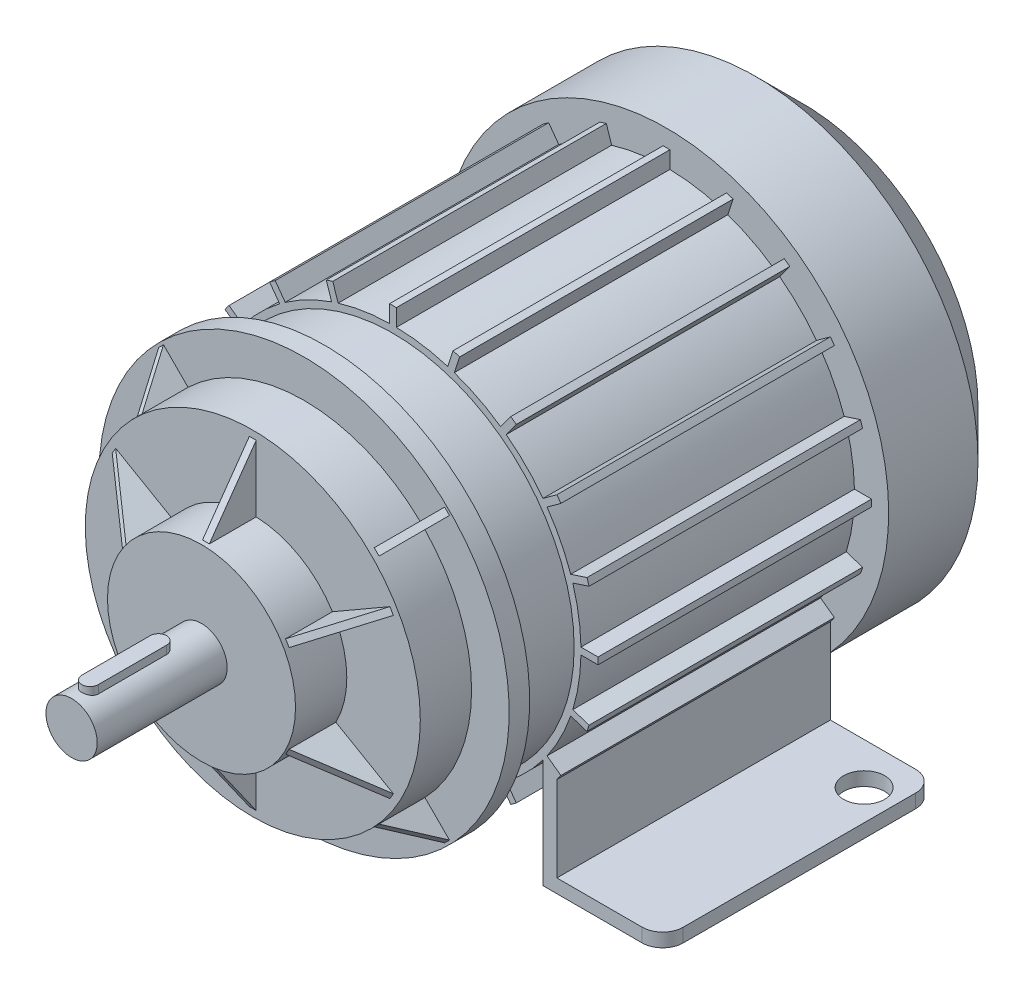
SolidWorks part; units mm, degrees
ref_plane "Front Plane" through (0, 0, 0) normal (0, 0, 1) x (1, 0, 0)
ref_plane "Top Plane" through (0, 0, 0) normal (0, 1, 0) x (1, 0, 0)
ref_plane "Right Plane" through (0, 0, 0) normal (1, 0, 0) x (0, 0, -1)
sketch "Sketch1" plane through (0, 0, 0) normal (0, 0, 1) x (1, 0, 0)
  circle A0 centre (0, 0) radius 82.55
  dimension "D1" = 165.1
extrude "Boss-Extrude1" add sketch "Sketch1" along normal blind 50.8 contours A0
chamfer "Chamfer1" distance 17.62 angle 45 1 edges at (82.55, 0, 0)
sketch "Sketch2" plane through (0, 0, 50.8) normal (0, 0, 1) x (1, 0, 0)
  line L0 (0, 69.85) -> (0, 76.2) construction
  line L1 (1.27, 76.1894) -> (1.27, 69.8385)
  line L2 (-1.27, 76.1894) -> (-1.27, 69.8385)
  line L3 (76.1894, 1.27) -> (69.8385, 1.27)
  line L4 (76.1894, -1.27) -> (69.8385, -1.27)
  line L5 (1.27, -76.1894) -> (1.27, -69.8385)
  line L6 (-1.27, -76.1894) -> (-1.27, -69.8385)
  line L7 (-76.1894, -1.27) -> (-69.8385, -1.27)
  line L8 (-76.1894, 1.27) -> (-69.8385, 1.27)
  line L9 (22.336, 72.8529) -> (20.3734, 66.8128)
  line L10 (24.7517, 72.068) -> (22.7891, 66.0279)
  line L11 (43.7556, 62.385) -> (40.0226, 57.247)
  line L12 (45.8105, 60.892) -> (42.0775, 55.754)
  line L13 (60.892, 45.8105) -> (55.754, 42.0775)
  line L14 (62.385, 43.7556) -> (57.247, 40.0226)
  line L15 (72.068, 24.7517) -> (66.0279, 22.7891)
  line L16 (72.8529, 22.336) -> (66.8128, 20.3734)
  line L17 (76.1894, 1.27) -> (69.8385, 1.27)
  line L18 (76.1894, -1.27) -> (69.8385, -1.27)
  line L19 (72.8529, -22.336) -> (66.8128, -20.3734)
  line L20 (72.068, -24.7517) -> (66.0279, -22.7891)
  line L21 (62.385, -43.7556) -> (57.247, -40.0226)
  line L22 (60.892, -45.8105) -> (55.754, -42.0775)
  line L23 (45.8105, -60.892) -> (42.0775, -55.754)
  line L24 (43.7556, -62.385) -> (40.0226, -57.247)
  line L25 (24.7517, -72.068) -> (22.7891, -66.0279)
  line L26 (22.336, -72.8529) -> (20.3734, -66.8128)
  line L27 (1.27, -76.1894) -> (1.27, -69.8385)
  line L28 (-1.27, -76.1894) -> (-1.27, -69.8385)
  line L29 (-22.336, -72.8529) -> (-20.3734, -66.8128)
  line L30 (-24.7517, -72.068) -> (-22.7891, -66.0279)
  line L31 (-43.7556, -62.385) -> (-40.0226, -57.247)
  line L32 (-45.8105, -60.892) -> (-42.0775, -55.754)
  line L33 (-60.892, -45.8105) -> (-55.754, -42.0775)
  line L34 (-62.385, -43.7556) -> (-57.247, -40.0226)
  line L35 (-72.068, -24.7517) -> (-66.0279, -22.7891)
  line L36 (-72.8529, -22.336) -> (-66.8128, -20.3734)
  line L37 (-76.1894, -1.27) -> (-69.8385, -1.27)
  line L38 (-76.1894, 1.27) -> (-69.8385, 1.27)
  line L39 (-72.8529, 22.336) -> (-66.8128, 20.3734)
  line L40 (-72.068, 24.7517) -> (-66.0279, 22.7891)
  line L41 (-62.385, 43.7556) -> (-57.247, 40.0226)
  line L42 (-60.892, 45.8105) -> (-55.754, 42.0775)
  line L43 (-45.8105, 60.892) -> (-42.0775, 55.754)
  line L44 (-43.7556, 62.385) -> (-40.0226, 57.247)
  line L45 (-24.7517, 72.068) -> (-22.7891, 66.0279)
  line L46 (-22.336, 72.8529) -> (-20.3734, 66.8128)
  arc A0 (-60.892, 45.8105) -> (-62.385, 43.7556) centre (0, 0) ccw
  arc A1 (-42.0775, 55.754) -> (-55.754, 42.0775) centre (0, 0) ccw
  arc A2 (-43.7556, 62.385) -> (-45.8105, 60.892) centre (0, 0) ccw
  arc A3 (-57.247, 40.0226) -> (-66.0279, 22.7891) centre (0, 0) ccw
  arc A4 (-22.336, 72.8529) -> (-24.7517, 72.068) centre (0, 0) ccw
  arc A5 (-22.7891, 66.0279) -> (-40.0226, 57.247) centre (0, 0) ccw
  arc A6 (-1.27, 69.8385) -> (-20.3734, 66.8128) centre (0, 0) ccw
  arc A7 (1.27, 76.1894) -> (-1.27, 76.1894) centre (0, 0) ccw
  arc A8 (24.7517, 72.068) -> (22.336, 72.8529) centre (0, 0) ccw
  arc A9 (45.8105, 60.892) -> (43.7556, 62.385) centre (0, 0) ccw
  arc A10 (20.3734, 66.8128) -> (1.27, 69.8385) centre (0, 0) ccw
  arc A11 (62.385, 43.7556) -> (60.892, 45.8105) centre (0, 0) ccw
  arc A12 (72.8529, 22.336) -> (72.068, 24.7517) centre (0, 0) ccw
  arc A13 (40.0226, 57.247) -> (22.7891, 66.0279) centre (0, 0) ccw
  arc A14 (55.754, 42.0775) -> (42.0775, 55.754) centre (0, 0) ccw
  arc A15 (66.0279, 22.7891) -> (57.247, 40.0226) centre (0, 0) ccw
  arc A16 (60.892, -45.8105) -> (62.385, -43.7556) centre (0, 0) ccw
  arc A17 (72.068, -24.7517) -> (72.8529, -22.336) centre (0, 0) ccw
  arc A18 (76.1894, -1.27) -> (76.1894, 1.27) centre (0, 0) ccw
  arc A19 (66.8128, -20.3734) -> (69.8385, -1.27) centre (0, 0) ccw
  arc A20 (69.8385, 1.27) -> (66.8128, 20.3734) centre (0, 0) ccw
  arc A21 (57.247, -40.0226) -> (66.0279, -22.7891) centre (0, 0) ccw
  arc A22 (42.0775, -55.754) -> (55.754, -42.0775) centre (0, 0) ccw
  arc A23 (22.7891, -66.0279) -> (40.0226, -57.247) centre (0, 0) ccw
  arc A24 (-66.8128, 20.3734) -> (-69.8385, 1.27) centre (0, 0) ccw
  arc A25 (-72.068, 24.7517) -> (-72.8529, 22.336) centre (0, 0) ccw
  arc A26 (-72.8529, -22.336) -> (-72.068, -24.7517) centre (0, 0) ccw
  arc A27 (-66.0279, -22.7891) -> (-57.247, -40.0226) centre (0, 0) ccw
  arc A28 (-62.385, -43.7556) -> (-60.892, -45.8105) centre (0, 0) ccw
  arc A29 (-45.8105, -60.892) -> (-43.7556, -62.385) centre (0, 0) ccw
  arc A30 (-55.754, -42.0775) -> (-42.0775, -55.754) centre (0, 0) ccw
  arc A31 (-40.0226, -57.247) -> (-22.7891, -66.0279) centre (0, 0) ccw
  arc A32 (-24.7517, -72.068) -> (-22.336, -72.8529) centre (0, 0) ccw
  arc A33 (-1.27, -76.1894) -> (1.27, -76.1894) centre (0, 0) ccw
  arc A34 (22.336, -72.8529) -> (24.7517, -72.068) centre (0, 0) ccw
  arc A35 (1.27, -69.8385) -> (20.3734, -66.8128) centre (0, 0) ccw
  arc A36 (-20.3734, -66.8128) -> (-1.27, -69.8385) centre (0, 0) ccw
  arc A37 (43.7556, -62.385) -> (45.8105, -60.892) centre (0, 0) ccw
  arc A38 (-69.8385, -1.27) -> (-66.8128, -20.3734) centre (0, 0) ccw
  arc A39 (-76.1894, 1.27) -> (-76.1894, -1.27) centre (0, 0) ccw
  point P25 (0, 0)
  point P102 (0, 0)
  dimension "D1" = 152.4
  dimension "D2" = 139.7
  dimension "D3" = 1.27
  dimension "D4" = 4
  dimension "D5" = 20
extrude "Boss-Extrude2" add sketch "Sketch2" along normal blind 101.6 contours L8 A39 L7 A38 L36 A26 L35 A27 L34 A28 L33 A30 L32 A29 L31 A31 L30 A32 L29 A36 L6 A33 L5 A35 L26 A34 L25 A23 L24 A37 L23 A22 L22 A16 L21 A21 L20 A17 L19 A19 L4 A18 L3 A20 L16 A12 L15 A15 L14 A11 L13
sketch "Sketch19" plane through (0, 0, 50.8) normal (0, 0, 1) x (1, 0, 0)
  line L0 (60.892, -45.8105) -> (55.754, -42.0775) construction
  line L1 (60.892, -45.8105) -> (55.754, -42.0775)
  line L2 (0, -82.55) -> (100.204, -82.55) construction
  line L3 (55.754, -42.0775) -> (55.754, -82.55)
  line L4 (55.754, -82.55) -> (100.204, -82.55)
  line L5 (100.204, -82.55) -> (100.204, -77.47)
  line L6 (100.204, -77.47) -> (60.892, -77.47)
  line L7 (60.892, -77.47) -> (60.892, -45.8105)
  line L8 (0, 0) -> (0, -82.55) construction
  line L9 (-100.204, -82.55) -> (-100.204, -77.47)
  line L10 (-55.754, -82.55) -> (-100.204, -82.55)
  line L11 (-100.204, -77.47) -> (-60.892, -77.47)
  line L12 (-60.892, -77.47) -> (-60.892, -45.8105)
  line L13 (-60.892, -45.8105) -> (-55.754, -42.0775)
  line L14 (-55.754, -42.0775) -> (-55.754, -82.55)
  circle A0 centre (0, 0) radius 82.55 construction
  dimension "D1" = 5.08
  dimension "D2" = 44.45
  dimension "D3" = 40.4725
extrude "Boss-Extrude8" add sketch "Sketch19" along normal up to surface (101.6 mm away) up to face at (0, 0, 152.4)
fillet "Fillet1" radius 7.62 4 edges at (-100.204, -80.01, 50.8) (-100.204, -80.01, 152.4) (100.204, -80.01, 50.8) (100.204, -80.01, 152.4)
sketch "Sketch4" plane through (0, 0, 152.4) normal (0, 0, 1) x (1, 0, 0)
  circle A0 centre (0, 0) radius 67.31
  dimension "D1" = 134.62
extrude "Boss-Extrude3" add sketch "Sketch4" along normal blind 25.4
sketch "Sketch5" plane through (0, 0, 177.8) normal (0, 0, 1) x (1, 0, 0)
  circle A0 centre (0, 0) radius 76.2
extrude "Boss-Extrude4" add sketch "Sketch5" along normal blind 7.62
sketch "Sketch6" plane through (0, 0, 185.42) normal (0, 0, 1) x (1, 0, 0)
  circle A0 centre (0, 0) radius 62.23
  dimension "D1" = 124.46
extrude "Boss-Extrude5" add sketch "Sketch6" along normal blind 19.05
sketch "Sketch8" plane through (0, 0, 204.47) normal (0, 0, 1) x (1, 0, 0)
  circle A0 centre (0, 0) radius 34.925
  dimension "D1" = 69.85
extrude "Boss-Extrude6" add sketch "Sketch8" along normal blind 19.05
ref_plane "Plane1" through (0, 0, 0) normal (1, 0, 0) x (0, 0, -1)
sketch "Sketch15" plane through (0, 0, 0) normal (1, 0, 0) x (0, 0, -1)
  line L0 (-223.52, 32.5953) -> (-204.47, 32.5953) construction
  line L1 (-223.52, 34.925) -> (-223.52, -34.925) construction
  line L2 (-204.47, 34.925) -> (-204.47, -34.925) construction
  line L3 (-204.47, 32.5953) -> (-202.6512, 32.5953) construction
  line L4 (-202.6512, 32.5953) -> (-202.6512, 62.1305) construction
  line L5 (-204.47, 62.23) -> (-204.47, -62.23) construction
  line L6 (-204.47, 34.925) -> (-223.52, 34.925) construction
  line L7 (-223.52, 32.5953) -> (-202.6512, 62.1305)
  dimension "D1" = 1.8188
  dimension "D2" = 2.3297
  dimension "D3" = 29.5352
rib "Rib9" sketch "Sketch15" sketch "Sketch15" thickness 2.54 extrusion direction parallel to sketch draft on no parameters "D1"=2.54
pattern_circular "CirPattern1" count 6 over 360 about axis through (0, 0, 0) along (0, 0, 1) of "Rib9"
sketch "Sketch16" plane through (0, 0, 0) normal (1, 0, 0) x (0, 0, -1)
  line L0 (-262.2923, 0) -> (62.6805, 0) construction
ref_plane "Plane2" through (0, 0, 0) normal (0.7071, -0.7071, 0) x (0, 0, -1)
sketch "Sketch17" plane through (0, 0, 0) normal (0.7071, -0.7071, 0) x (0, 0, -1)
  line L0 (-204.47, 60.7051) -> (-183.9829, 60.7051) construction
  line L1 (-204.47, 62.23) -> (-204.47, -62.23) construction
  line L2 (-183.9829, 60.7051) -> (-183.9829, 76.2) construction
  line L4 (-262.2923, 0) -> (62.6805, 0) construction
  line L5 (-204.47, 60.7051) -> (-183.9829, 76.2)
  dimension "D1" = 20.4871
  dimension "D2" = 60.7051
  dimension "D3" = 15.4949
rib "Rib10" sketch "Sketch17" sketch "Sketch17" thickness 2.54 extrusion direction parallel to sketch draft on no parameters "D1"=2.54
pattern_circular "CirPattern2" count 4 over 360 about axis through (0, 0, 0) along (0, 0, 1) of "Rib10"
sketch "Sketch18" plane through (0, 0, 223.52) normal (0, 0, 1) x (1, 0, 0)
  circle A0 centre (0, 0) radius 9.525
  dimension "D1" = 19.05
extrude "Boss-Extrude7" add sketch "Sketch18" along normal blind 48.26
sketch "Sketch20" plane through (0, -77.47, 0) normal (0, 1, 0) x (1, 0, 0)
  line L0 (88.8598, -50.8) -> (88.8598, -66.2277) construction
  line L1 (92.584, -50.8) -> (60.892, -50.8) construction
  line L2 (88.8598, -66.2277) -> (100.204, -66.2277) construction
  line L3 (100.204, -144.78) -> (100.204, -58.42) construction
  circle A0 centre (88.8598, -66.2277) radius 7.6228
  dimension "D3" = 15.2456
  dimension "D1" = 11.3442
  dimension "D2" = 15.4277
extrude "Cut-Extrude1" cut sketch "Sketch20" against normal through all
mirror "Mirror1" about plane through (0, 0, 0) normal (1, 0, 0) of "Cut-Extrude1"
sketch "Sketch21" plane through (0, 0, 0) normal (0, 1, 0) x (1, 0, 0)
  line L0 (0, -286.2576) -> (0, -223.52) construction
  line L1 (-9.525, -223.52) -> (9.525, -223.52) construction
  line L2 (0, -264.922) -> (0, -239.522) construction
  line L3 (-3.048, -264.922) -> (-3.048, -239.522)
  line L4 (3.048, -264.922) -> (3.048, -239.522)
  line L5 (-9.525, -271.78) -> (9.525, -271.78) construction
  arc A0 (-3.048, -264.922) -> (3.048, -264.922) centre (0, -264.922) ccw
  arc A1 (3.048, -239.522) -> (-3.048, -239.522) centre (0, -239.522) ccw
  point P6 (0, -252.222)
  point P13 (0, -267.97)
  point P14 (0, -236.474)
  dimension "D1" = 6.096
  dimension "D2" = 3.81
  dimension "D3" = 31.496
extrude "Boss-Extrude9" add sketch "Sketch21" along normal blind 12.065
